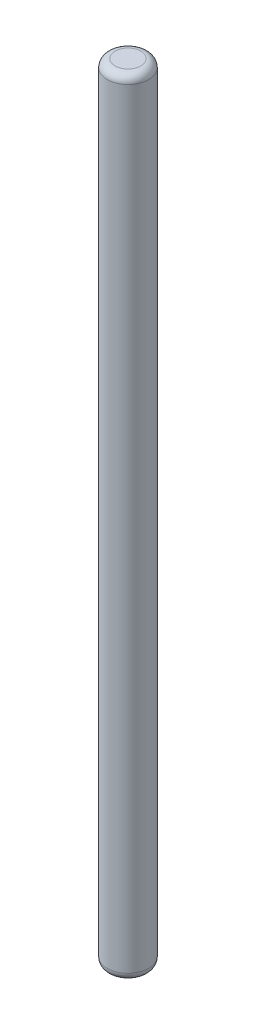
SolidWorks part; units mm, degrees
material "Chrome Stainless Steel"
ref_plane "Front Plane" through (0, 0, 0) normal (0, 0, 1) x (1, 0, 0)
ref_plane "Top Plane" through (0, 0, 0) normal (0, 1, 0) x (1, 0, 0)
ref_plane "Right Plane" through (0, 0, 0) normal (1, 0, 0) x (0, 0, -1)
sketch "Sketch1" plane through (0, 0, 0) normal (0, 1, 0) x (1, 0, 0)
  circle A0 centre (0, 0) radius 1.0033
  dimension "D1" = 2.0066
extrude "Boss-Extrude1" add sketch "Sketch1" along normal blind 37.9984
fillet "Fillet1" radius 0.381 2 edges at (0, 0, 1.0033) (0, 37.9984, 1.0033)
